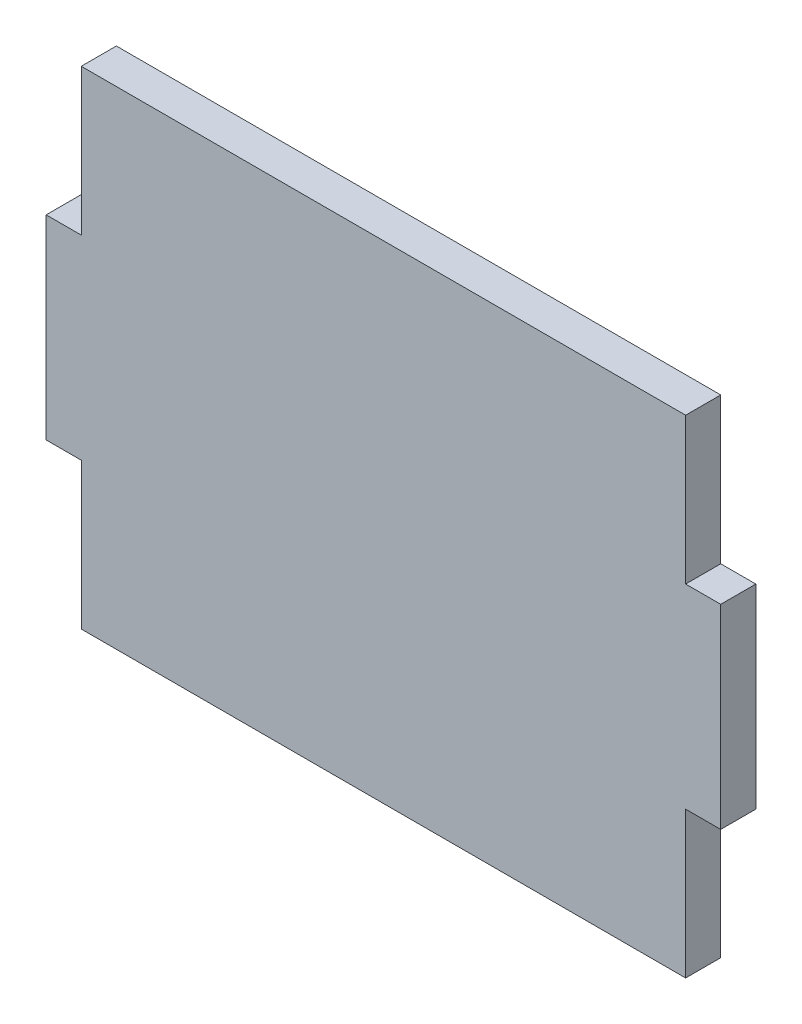
SolidWorks part; units mm, degrees
ref_plane "Front Plane" through (0, 0, 0) normal (0, 0, 1) x (1, 0, 0)
ref_plane "Top Plane" through (0, 0, 0) normal (0, 1, 0) x (1, 0, 0)
ref_plane "Right Plane" through (0, 0, 0) normal (1, 0, 0) x (0, 0, -1)
sketch "Sketch1" plane through (0, 0, 0) normal (0, 0, 1) x (1, 0, 0)
  line L0 (0, -175) -> (0, -250)
  line L1 (0, 0) -> (310, 0)
  line L2 (0, 0) -> (0, -75)
  line L3 (0, -250) -> (310, -250)
  line L4 (310, 0) -> (310, -75)
  line L5 (-18, -75) -> (0, -75)
  line L6 (-18, -75) -> (-18, -175)
  line L7 (-18, -175) -> (0, -175)
  line L9 (155, 0) -> (155, -252.8147) construction
  line L10 (328, -175) -> (310, -175)
  line L11 (328, -75) -> (328, -175)
  line L12 (328, -75) -> (310, -75)
  line L13 (310, -175) -> (310, -250)
  point P5 (0, -125)
  dimension "D1" = 250
  dimension "D2" = 310
  dimension "D3" = 100
extrude "Boss-Extrude2" add sketch "Sketch1" along normal blind 18
